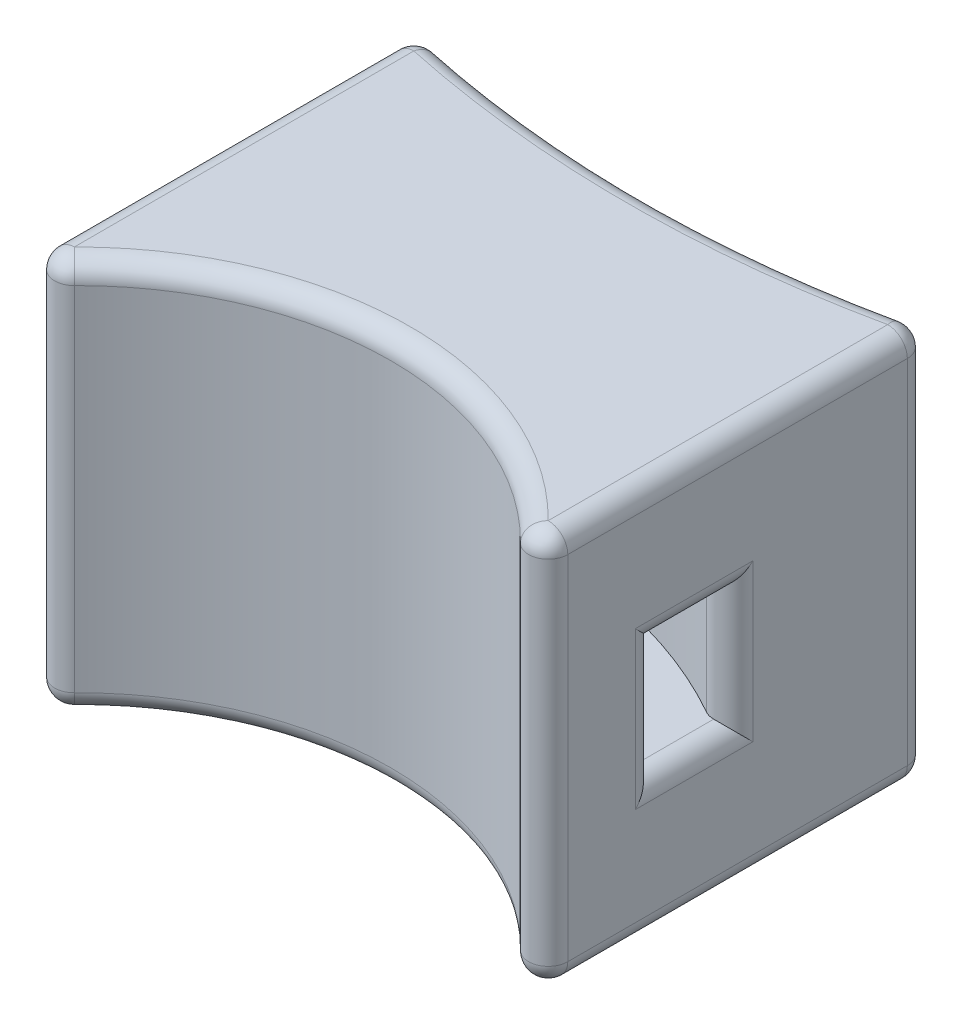
SolidWorks part; units mm, degrees
ref_plane "Front Plane" through (0, 0, 0) normal (0, 0, 1) x (1, 0, 0)
ref_plane "Top Plane" through (0, 0, 0) normal (0, 1, 0) x (1, 0, 0)
ref_plane "Right Plane" through (0, 0, 0) normal (1, 0, 0) x (0, 0, -1)
sketch "Sketch1" plane through (0, 0, 0) normal (0, 1, 0) x (1, 0, 0)
  line L0 (-13.0971, 30.5263) -> (-13.0971, 9.1906)
  line L1 (13.0971, 30.5263) -> (13.0971, 9.1906)
  line L2 (0, 85.9542) -> (0, 0) construction
  line L3 (-15.1502, 5.1452) -> (-13.0971, 11.1906) construction
  line L4 (-28.25, 36.5) -> (28.25, 36.5) construction
  circle A0 centre (0, 0) radius 16 construction
  circle A1 centre (0, 85.9542) radius 56.9542 construction
  arc A2 (-13.0971, 9.1906) -> (13.0971, 9.1906) centre (0, 0) cw
  arc A3 (-13.0971, 30.5263) -> (13.0971, 30.5263) centre (0, 85.9542) ccw
  circle A4 centre (0, 6.7427) radius 13.8317 construction
  circle A5 centre (0, 6.7427) radius 16.8317 construction
  point P9 (0, 29)
  point P10 (0, 16)
  point P11 (13.0971, 11.1906)
  point P12 (0, 29)
  point P16 (0, 23.5744)
  dimension "D2" = 56.5
  dimension "D3" = 32
  dimension "D5" = 3
  dimension "D1" = 13
  dimension "D4" = 26.1941
  dimension "D6" = 2
  dimension "D7" = 7.5
extrude "Boss-Extrude1" add sketch "Sketch1" along normal blind 20
sketch "Sketch2" plane through (0, 0, 0) normal (1, 0, 0) x (0, 0, -1)
  line L0 (23.5744, 0) -> (23.5744, 20) construction
  line L1 (20.5744, 13) -> (23.5744, 13)
  line L2 (20.5744, 13) -> (20.5744, 7)
  line L3 (20.5744, 7) -> (23.5744, 7)
  line L4 (23.5744, 13) -> (23.5744, 7)
  line L5 (20.5744, 20) -> (20.5744, 0) construction
  line L6 (85.9542, 0) -> (0, 0) construction
  line L7 (20.5744, 0) -> (-7.0891, 0) construction
  line L8 (30.5263, 20) -> (29, 20) construction
  line L9 (0, 0) -> (0, 13.0196) construction
  point P22 (20.5744, 10)
  dimension "D1" = 6
revolve "Cut-Revolve1" cut sketch "Sketch2" angle 360 about L9
fillet "Fillet1" radius 1 20 edges at (0, 20, -16) (0, 0, -16) (13.0971, 10, -9.1906) (13.0971, 20, -19.8585) (13.0971, 0, -19.8585) (13.0971, 10, -19.6015) (13.0971, 13, -17.7345) (13.0971, 10, -15.8674) (13.0971, 7, -17.7345) (13.0971, 10, -30.5263) (0, 20, -29) (0, 0, -29) (-13.0971, 10, -30.5263) (-13.0971, 20, -19.8585) (-13.0971, 10, -9.1906) (-13.0971, 0, -19.8585) (-13.0971, 10, -19.6015) (-13.0971, 7, -17.7345) (-13.0971, 10, -15.8674) (-13.0971, 13, -17.7345)
